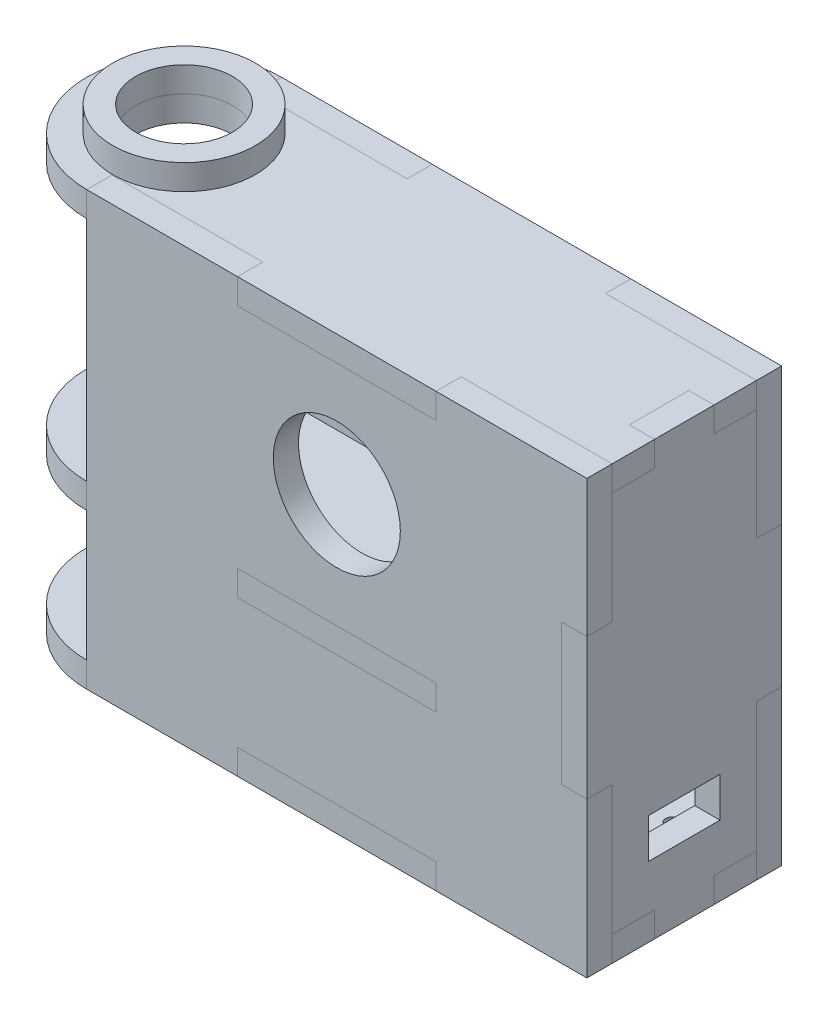
SolidWorks part; units mm, degrees
ref_plane "前视基准面" through (0, 0, 0) normal (0, 0, 1) x (1, 0, 0)
ref_plane "上视基准面" through (0, 0, 0) normal (0, 1, 0) x (1, 0, 0)
ref_plane "右视基准面" through (0, 0, 0) normal (1, 0, 0) x (0, 0, -1)
other "Configuration Table"
sketch "草图3" plane through (0, 0, 0) normal (0, 0, 1) x (1, 0, 0)
  line L0 (31.5, 17.5) -> (31.5, -37)
  line L1 (-31.5, -17.5) -> (31.5, -17.5)
  line L2 (-31.5, -17.5) -> (-31.5, 17.5)
  line L3 (-31.5, 17.5) -> (31.5, 17.5)
  line L4 (31.5, -17.5) -> (31.5, 17.5) construction
  line L5 (-31.5, -17.5) -> (31.5, 17.5) construction
  line L6 (-31.5, 17.5) -> (31.5, -17.5) construction
  line L7 (-31.5, -17.5) -> (31.5, -17.5)
  line L8 (-31.5, -17.5) -> (-31.5, -37)
  line L9 (-31.5, -37) -> (31.5, -37)
  line L10 (31.5, -17.5) -> (31.5, -37) construction
  line L11 (-12.5, -33.825) -> (12.5, -33.825)
  line L12 (-12.5, -33.825) -> (-12.5, -40.175)
  line L13 (-12.5, -40.175) -> (12.5, -40.175)
  line L14 (12.5, -33.825) -> (12.5, -40.175)
  line L15 (-12.5, -33.825) -> (12.5, -40.175) construction
  line L16 (-12.5, -40.175) -> (12.5, -33.825) construction
  line L18 (28.325, -19.75) -> (34.675, -19.75)
  line L19 (28.325, -19.75) -> (28.325, 0.25)
  line L20 (28.325, 0.25) -> (34.675, 0.25)
  line L21 (34.675, -19.75) -> (34.675, 0.25)
  line L22 (28.325, -19.75) -> (34.675, 0.25) construction
  line L23 (28.325, 0.25) -> (34.675, -19.75) construction
  line L24 (-12.5, 20.675) -> (12.5, 20.675)
  line L25 (-12.5, 20.675) -> (-12.5, 14.325)
  line L26 (-12.5, 14.325) -> (12.5, 14.325)
  line L27 (12.5, 20.675) -> (12.5, 14.325)
  line L28 (-12.5, 20.675) -> (12.5, 14.325) construction
  line L29 (-12.5, 14.325) -> (12.5, 20.675) construction
  circle A0 centre (0, 0) radius 8
  point P10 (0, -37)
  point P15 (31.5, -9.75)
  point P20 (0, 17.5)
  dimension "D1" = 20
  dimension "D5" = 16
  dimension "D2" = 25
  dimension "D3" = 25
  dimension "D4" = 54.5
  dimension "D6" = 63
  dimension "D7" = 6.35
  dimension "D8" = 6.35
extrude "凸台-拉伸2" add sketch "草图3" along normal blind 3.175 contours A0 L6 L2 L1 L19 | A0 L6 L19 L20 L0 L3 L27 L26 L25 | L18 L19 L1 L8 L9 L12 L11 L14 L0
pattern_linear "阵列(线性)1" count 2 spacing 21.35 along (0, 0, -1) of bodies 107
sketch "草图4" plane through (0, 0, -21.35) normal (0, 0, -1) x (-1, 0, 0)
  line L0 (0, -37) -> (0, -15.9125) construction
  line L2 (-12.5, -14.325) -> (12.5, -14.325)
  line L3 (-12.5, -14.325) -> (-12.5, -17.5)
  line L4 (-12.5, -17.5) -> (12.5, -17.5)
  line L5 (12.5, -14.325) -> (12.5, -17.5)
  line L6 (-12.5, -14.325) -> (12.5, -17.5) construction
  line L7 (-12.5, -17.5) -> (12.5, -14.325) construction
  line L16 (31.5, 17.5) -> (12.5, 17.5)
  line L17 (12.5, 17.5) -> (12.5, 14.325)
  line L18 (12.5, 14.325) -> (-12.5, 14.325)
  line L19 (-12.5, 14.325) -> (-12.5, 17.5)
  line L20 (-12.5, 17.5) -> (-31.5, 17.5)
  line L21 (-31.5, 17.5) -> (-31.5, 0.25)
  line L22 (-31.5, 0.25) -> (-28.325, 0.25)
  line L23 (-28.325, 0.25) -> (-28.325, -17.5)
  line L24 (-28.325, -17.5) -> (-31.5, -17.5)
  line L25 (-31.5, -17.5) -> (-31.5, -37)
  line L26 (-31.5, -37) -> (-12.5, -37)
  line L27 (-12.5, -37) -> (-12.5, -33.825)
  line L28 (-12.5, -33.825) -> (12.5, -33.825)
  line L29 (12.5, -33.825) -> (12.5, -37)
  line L30 (12.5, -37) -> (31.5, -37)
  line L31 (31.5, -37) -> (31.5, 17.5)
  line L32 (31.5, 17.5) -> (12.5, 17.5) construction
  line L33 (12.5, 17.5) -> (12.5, 14.325) construction
  line L34 (12.5, 14.325) -> (-12.5, 14.325) construction
  line L35 (-12.5, 14.325) -> (-12.5, 17.5) construction
  line L36 (-12.5, 17.5) -> (-31.5, 17.5) construction
  line L37 (-31.5, 17.5) -> (-31.5, 0.25) construction
  line L38 (-31.5, 0.25) -> (-28.325, 0.25) construction
  line L39 (-28.325, 0.25) -> (-28.325, -17.5) construction
  line L41 (-31.5, -17.5) -> (-31.5, -37) construction
  line L42 (-31.5, -37) -> (-12.5, -37) construction
  line L43 (-12.5, -37) -> (-12.5, -33.825) construction
  line L44 (-12.5, -33.825) -> (12.5, -33.825) construction
  line L45 (12.5, -33.825) -> (12.5, -37) construction
  line L46 (12.5, -37) -> (31.5, -37) construction
  line L47 (31.5, -37) -> (31.5, 17.5) construction
  line L55 (-28.325, -17.5) -> (-31.5, -17.5)
  dimension "D2" = 21.0875
  dimension "D3" = 25
  dimension "D1" = 0
extrude "切除-拉伸1" cut sketch "草图4" against normal through all contours L5 L2 L3 L4
sketch "草图5" plane through (0, 14.325, 0) normal (0, 1, 0) x (1, 0, 0)
  line L0 (-31.5, 18.175) -> (-31.5, 21.35) construction
  line L1 (-31.5, 18.175) -> (31.5, 18.175)
  line L2 (-31.5, 21.35) -> (-31.5, -3.175)
  line L3 (-31.5, 0) -> (31.5, 0)
  line L4 (12.5, 21.35) -> (-12.5, 21.35)
  line L5 (-12.5, 21.35) -> (-12.5, 18.175)
  line L6 (-12.5, 18.175) -> (12.5, 18.175)
  line L7 (12.5, 18.175) -> (12.5, 21.35)
  line L8 (12.5, 21.35) -> (-12.5, 21.35)
  line L9 (-12.5, 21.35) -> (-12.5, 18.175)
  line L10 (-12.5, 18.175) -> (12.5, 18.175)
  line L11 (12.5, 18.175) -> (12.5, 21.35)
  line L12 (12.5, 0) -> (-12.5, 0)
  line L13 (-12.5, 0) -> (-12.5, -3.175)
  line L14 (-12.5, -3.175) -> (12.5, -3.175)
  line L15 (12.5, -3.175) -> (12.5, 0)
  line L16 (12.5, 0) -> (-12.5, 0)
  line L17 (-12.5, 0) -> (-12.5, -3.175)
  line L18 (-12.5, -3.175) -> (12.5, -3.175)
  line L19 (12.5, -3.175) -> (12.5, 0)
  line L20 (31.5, 18.175) -> (31.5, 0)
  line L22 (28.325, 5.3375) -> (34.675, 5.3375)
  line L23 (28.325, 5.3375) -> (28.325, 12.8375)
  line L24 (28.325, 12.8375) -> (34.675, 12.8375)
  line L25 (34.675, 5.3375) -> (34.675, 12.8375)
  line L26 (28.325, 5.3375) -> (34.675, 12.8375) construction
  line L27 (28.325, 12.8375) -> (34.675, 5.3375) construction
  arc A0 (-31.5, -3.175) -> (-31.5, 21.35) centre (-31.5, 9.0875) cw
  point P20 (31.5, 9.0875)
  line M10 (12.5, 21.35) -> (-12.5, 21.35)
  line M11 (-12.5, 21.35) -> (-12.5, 18.175)
  line M12 (-12.5, 18.175) -> (12.5, 18.175)
  line M13 (12.5, 18.175) -> (12.5, 21.35)
  dimension "D1" = 0
  dimension "D2" = 0
extrude "凸台-拉伸3" add sketch "草图5" along normal blind 3.175 separate body contours L23 L24 L20 L1 L2 L3 L22 M12 | A0 L2 | M13 M10 M11 M12 | L18 L19 L3 L17
sketch "草图6" plane through (0, -14.325, 0) normal (0, -1, 0) x (1, 0, 0)
  line L0 (28.325, 0) -> (28.325, -18.175)
  line L4 (12.5, -18.175) -> (-12.5, -18.175)
  line L5 (-12.5, -18.175) -> (-12.5, -21.35)
  line L6 (-12.5, -21.35) -> (12.5, -21.35)
  line L7 (12.5, -21.35) -> (12.5, -18.175)
  line L8 (12.5, -18.175) -> (-12.5, -18.175)
  line L9 (-12.5, -18.175) -> (-12.5, -21.35)
  line L10 (-12.5, -21.35) -> (12.5, -21.35)
  line L11 (12.5, -21.35) -> (12.5, -18.175)
  line L12 (12.5, 0) -> (12.5, 3.175)
  line L13 (12.5, 3.175) -> (-12.5, 3.175)
  line L14 (-12.5, 3.175) -> (-12.5, 0)
  line L15 (-12.5, 0) -> (12.5, 0)
  line L16 (12.5, 0) -> (12.5, 3.175)
  line L17 (12.5, 3.175) -> (-12.5, 3.175)
  line L18 (-12.5, 3.175) -> (-12.5, 0)
  line L19 (-12.5, 0) -> (12.5, 0)
  line L33 (28.325, -12.8375) -> (28.325, -5.3375)
  line L34 (28.325, -5.3375) -> (31.5, -5.3375)
  line L35 (31.5, -5.3375) -> (31.5, 0)
  line L36 (31.5, 0) -> (12.5, 0)
  line L37 (12.5, 0) -> (12.5, 3.175)
  line L38 (12.5, 3.175) -> (-12.5, 3.175)
  line L39 (-12.5, 3.175) -> (-12.5, 0)
  line L40 (-12.5, 0) -> (-31.5, 0)
  line L41 (-31.5, 0) -> (-31.5, 3.175)
  line L42 (-31.5, -21.35) -> (-31.5, -18.175)
  line L43 (-31.5, -18.175) -> (-12.5, -18.175)
  line L44 (-12.5, -18.175) -> (-12.5, -21.35)
  line L45 (-12.5, -21.35) -> (12.5, -21.35)
  line L46 (12.5, -21.35) -> (12.5, -18.175)
  line L47 (12.5, -18.175) -> (31.5, -18.175)
  line L48 (31.5, -18.175) -> (31.5, -12.8375)
  line L49 (31.5, -12.8375) -> (28.325, -12.8375)
  line L50 (28.325, -12.8375) -> (28.325, -5.3375)
  line L51 (28.325, -5.3375) -> (31.5, -5.3375)
  line L52 (31.5, -5.3375) -> (31.5, 0)
  line L53 (31.5, 0) -> (12.5, 0)
  line L54 (12.5, 0) -> (12.5, 3.175)
  line L55 (12.5, 3.175) -> (-12.5, 3.175)
  line L56 (-12.5, 3.175) -> (-12.5, 0)
  line L57 (-12.5, 0) -> (-31.5, 0)
  line L58 (-31.5, 0) -> (-31.5, 3.175)
  line L59 (-31.5, -21.35) -> (-31.5, -18.175)
  line L60 (-31.5, -18.175) -> (-12.5, -18.175)
  line L61 (-12.5, -18.175) -> (-12.5, -21.35)
  line L62 (-12.5, -21.35) -> (12.5, -21.35)
  line L63 (12.5, -21.35) -> (12.5, -18.175)
  line L64 (12.5, -18.175) -> (31.5, -18.175)
  line L65 (31.5, -18.175) -> (31.5, -12.8375)
  line L66 (31.5, -12.8375) -> (28.325, -12.8375)
  arc A1 (-31.5, 3.175) -> (-31.5, -21.35) centre (-31.5, -9.0875) ccw
  arc A2 (-31.5, 3.175) -> (-31.5, -21.35) centre (-31.5, -9.0875) ccw
  line M27 (12.5, -18.175) -> (-12.5, -18.175)
  line M28 (-12.5, -18.175) -> (-12.5, -21.35)
  line M29 (-12.5, -21.35) -> (12.5, -21.35)
  line M30 (12.5, -21.35) -> (12.5, -18.175)
  dimension "D1" = 0
  dimension "D2" = 0
  dimension "D3" = 0
extrude "凸台-拉伸4" add sketch "草图6" along normal blind 3.175 separate body contours L58 A2 L59 L60 L64 L0 L53 L19 L57 M27 | M30 M27 M28 M29
sketch "草图7" plane through (0, -33.825, 0) normal (0, -1, 0) x (1, 0, 0)
  line L13 (-31.5, 0) -> (-31.5, 3.175)
  line L14 (-31.5, -21.35) -> (-31.5, -18.175)
  line L15 (-31.5, -18.175) -> (-12.5, -18.175)
  line L17 (-12.5, -21.35) -> (12.5, -21.35)
  line L18 (-31.5, -18.175) -> (-12.5, -18.175)
  line L19 (12.5, -18.175) -> (28.325, -18.175)
  line L20 (28.325, -18.175) -> (28.325, 0)
  line L22 (-12.5, -18.175) -> (-12.5, -21.35)
  line L23 (12.5, 3.175) -> (-12.5, 3.175)
  line L25 (-12.5, -18.175) -> (-12.5, -21.35)
  line L26 (-31.5, 0) -> (-31.5, 3.175)
  line L27 (-31.5, -21.35) -> (-31.5, -18.175)
  line L30 (-12.5, -21.35) -> (12.5, -21.35)
  line L32 (12.5, -18.175) -> (28.325, -18.175)
  line L36 (12.5, 3.175) -> (-12.5, 3.175)
  line L41 (12.5, -21.35) -> (12.5, -18.175)
  line L43 (28.325, -12.8375) -> (28.325, -5.3375)
  line L44 (31.5, -12.8375) -> (28.325, -12.8375)
  line L45 (31.5, -18.175) -> (31.5, -12.8375)
  line L46 (12.5, -18.175) -> (31.5, -18.175)
  line L47 (12.5, -21.35) -> (12.5, -18.175)
  line L48 (-12.5, -21.35) -> (12.5, -21.35)
  line L49 (-12.5, -18.175) -> (-12.5, -21.35)
  line L50 (-31.5, -18.175) -> (-12.5, -18.175)
  line L51 (-31.5, -21.35) -> (-31.5, -18.175)
  line L52 (-31.5, 0) -> (-31.5, 3.175)
  line L53 (-12.5, 0) -> (-31.5, 0)
  line L54 (-12.5, 3.175) -> (-12.5, 0)
  line L55 (12.5, 3.175) -> (-12.5, 3.175)
  line L56 (12.5, 0) -> (12.5, 3.175)
  line L57 (31.5, 0) -> (12.5, 0)
  line L58 (31.5, -5.3375) -> (31.5, 0)
  line L59 (28.325, -5.3375) -> (31.5, -5.3375)
  line L60 (28.325, -12.8375) -> (28.325, -5.3375)
  line L61 (31.5, -12.8375) -> (28.325, -12.8375)
  line L62 (31.5, -18.175) -> (31.5, -12.8375)
  line L63 (12.5, -18.175) -> (31.5, -18.175)
  line L64 (12.5, -21.35) -> (12.5, -18.175)
  line L65 (-12.5, -21.35) -> (12.5, -21.35)
  line L66 (-12.5, -18.175) -> (-12.5, -21.35)
  line L67 (-31.5, -18.175) -> (-12.5, -18.175)
  line L68 (-31.5, -21.35) -> (-31.5, -18.175)
  line L69 (-31.5, 0) -> (-31.5, 3.175)
  line L70 (-12.5, 0) -> (-31.5, 0)
  line L71 (-12.5, 3.175) -> (-12.5, 0)
  line L72 (12.5, 3.175) -> (-12.5, 3.175)
  line L73 (12.5, 0) -> (12.5, 3.175)
  line L74 (31.5, 0) -> (12.5, 0)
  line L75 (31.5, -5.3375) -> (31.5, 0)
  line L76 (28.325, -5.3375) -> (31.5, -5.3375)
  line L77 (12.5, -21.35) -> (12.5, -18.175)
  line L79 (28.325, 0) -> (12.5, 0)
  line L81 (28.325, 0) -> (12.5, 0)
  line L82 (12.5, 0) -> (12.5, 3.175)
  line L83 (12.5, 0) -> (12.5, 3.175)
  line L84 (-12.5, 3.175) -> (-12.5, 0)
  line L85 (-12.5, 3.175) -> (-12.5, 0)
  line L86 (-12.5, 0) -> (-31.5, 0)
  line L87 (-12.5, 0) -> (-31.5, 0)
  line L88 (28.325, -18.175) -> (28.325, 0)
  arc A1 (-31.5, 3.175) -> (-31.5, -21.35) centre (-31.5, -9.0875) ccw
  arc A2 (-31.5, 3.175) -> (-31.5, -21.35) centre (-31.5, -9.0875) ccw
  arc A3 (-31.5, 3.175) -> (-31.5, -21.35) centre (-31.5, -9.0875) ccw
  arc A4 (-31.5, 3.175) -> (-31.5, -21.35) centre (-31.5, -9.0875) ccw
  line M33 (-12.5, 0) -> (12.5, 0)
  line M34 (12.5, 0) -> (12.5, 3.175)
  line M35 (12.5, 3.175) -> (-12.5, 3.175)
  line M36 (-12.5, 3.175) -> (-12.5, 0)
  dimension "D1" = 0
  dimension "D2" = 0
extrude "凸台-拉伸5" add sketch "草图7" along normal blind 3.175 separate body contours L26 A2 L27 L18 L25 L30 L77 L32 L88 L81 L87 M33 | M36 M33 M34 M35 | L88 L76 L75 L74 | L88 L63 L62 L61
sketch "草图8" plane through (28.325, 0, 0) normal (1, 0, 0) x (0, 0, -1)
  line L38 (12.8375, -33.825) -> (5.3375, -33.825) construction
  line L39 (5.3375, -33.825) -> (5.3375, -37) construction
  line L40 (5.3375, -37) -> (12.8375, -37) construction
  line L41 (12.8375, -37) -> (12.8375, -33.825) construction
  line L43 (21.35, -17.5) -> (21.35, 0.25) construction
  line L44 (21.35, 0.25) -> (18.175, 0.25) construction
  line L45 (18.175, 0.25) -> (18.175, -17.5) construction
  line L46 (18.175, -17.5) -> (21.35, -17.5) construction
  line L47 (0, -17.5) -> (0, 0.25) construction
  line L48 (0, 0.25) -> (-3.175, 0.25) construction
  line L49 (-3.175, 0.25) -> (-3.175, -17.5) construction
  line L50 (-3.175, -17.5) -> (0, -17.5) construction
  line L51 (5.3375, 14.325) -> (12.8375, 14.325) construction
  line L52 (12.8375, 14.325) -> (12.8375, 17.5) construction
  line L53 (12.8375, 17.5) -> (5.3375, 17.5) construction
  line L54 (5.3375, 17.5) -> (5.3375, 14.325) construction
  line L55 (12.8375, -33.825) -> (5.3375, -33.825)
  line L56 (5.3375, -33.825) -> (5.3375, -37)
  line L57 (5.3375, -37) -> (12.8375, -37)
  line L58 (12.8375, -37) -> (12.8375, -33.825)
  line L59 (21.35, -17.5) -> (21.35, 0.25)
  line L60 (21.35, 0.25) -> (18.175, 0.25)
  line L61 (18.175, 0.25) -> (18.175, -17.5)
  line L62 (18.175, -17.5) -> (21.35, -17.5)
  line L63 (0, -17.5) -> (0, 0.25)
  line L64 (0, 0.25) -> (-3.175, 0.25)
  line L65 (-3.175, 0.25) -> (-3.175, -17.5)
  line L66 (-3.175, -17.5) -> (0, -17.5)
  line L67 (5.3375, 14.325) -> (12.8375, 14.325)
  line L68 (12.8375, 14.325) -> (12.8375, 17.5)
  line L69 (12.8375, 17.5) -> (5.3375, 17.5)
  line L70 (5.3375, 17.5) -> (5.3375, 14.325)
  line L71 (18.175, -17.5) -> (18.175, -37) construction
  line L72 (0, 14.325) -> (18.175, 14.325)
  line L73 (0, 14.325) -> (0, -33.825)
  line L74 (0, -33.825) -> (18.175, -33.825)
  line L75 (18.175, 14.325) -> (18.175, -33.825)
extrude "凸台-拉伸6" add sketch "草图8" along normal up to surface (3.175 mm away) separate body
sketch "草图12" plane through (0, -37, 0) normal (0, -1, 0) x (1, 0, 0)
  line L0 (31.5, -9.0875) -> (-43.7625, -9.0875) construction
  line L1 (-16.3955, -12.8375) -> (-16.3955, -5.3375) construction
  line L3 (31.5, -5.3375) -> (31.5, -12.8375) construction
  line L8 (22.7545, -9.0875) -> (26.2045, -9.0875) construction
  line L9 (-12.9455, -16.6875) -> (22.7545, -16.6875)
  line L10 (-12.9455, -16.6875) -> (-12.9455, -1.4875)
  line L11 (-12.9455, -1.4875) -> (22.7545, -1.4875)
  line L12 (22.7545, -16.6875) -> (22.7545, -1.4875)
  line L13 (-12.9455, -16.6875) -> (22.7545, -1.4875) construction
  line L14 (-12.9455, -1.4875) -> (22.7545, -16.6875) construction
  line L15 (26.2045, -12.8375) -> (26.2045, -5.3375) construction
  line L16 (4.9045, -9.0875) -> (4.9045, -3.4951) construction
  arc A0 (-31.5, 3.175) -> (-31.5, -21.35) centre (-31.5, -9.0875) ccw construction
  circle A1 centre (26.2045, -5.3375) radius 0.795
  circle A2 centre (26.2045, -12.8375) radius 0.795
  circle A3 centre (-16.3955, -12.8375) radius 0.795
  circle A4 centre (-16.3955, -5.3375) radius 0.795
  point P7 (4.9045, -9.0875)
  dimension "D1" = 15.2
  dimension "D4" = 1.59
  dimension "D2" = 35.7
  dimension "D3" = 3.45
  dimension "D5" = 7.5
extrude "切除-拉伸2" cut sketch "草图12" against normal through all
sketch "草图14" plane through (0, -33.825, 0) normal (0, 1, 0) x (1, 0, 0)
  line L0 (-12.9455, 16.6875) -> (22.7545, 1.4875) construction
  line L1 (4.9045, 9.0875) -> (27.6217, 9.0875) construction
  line L2 (28.325, 18.175) -> (28.325, 0)
  line L3 (4.9045, 9.0875) -> (4.9045, 14.677) construction
  line L4 (22.7545, 16.6875) -> (-12.9455, 16.6875)
  line L5 (22.7545, 1.4875) -> (22.7545, 16.6875)
  line L6 (-12.9455, 1.4875) -> (22.7545, 1.4875)
  line L7 (-12.9455, 16.6875) -> (-12.9455, 1.4875)
  line L8 (22.7545, 16.6875) -> (-12.9455, 16.6875)
  line L9 (22.7545, 1.4875) -> (22.7545, 16.6875)
  line L10 (-12.9455, 1.4875) -> (22.7545, 1.4875)
  line L11 (-12.9455, 16.6875) -> (-12.9455, 1.4875)
  line L12 (-18.5161, 5.3375) -> (-18.5161, 12.8375)
  line L13 (-18.5161, 18.175) -> (-18.5161, 0)
  line L14 (-12.5, 0) -> (12.5, 0)
  line L15 (12.5, 18.175) -> (-12.5, 18.175)
  line L17 (-31.5, -3.175) -> (-31.5, 0)
  line L18 (-31.5, 0) -> (-12.5, 0)
  line L19 (-12.5, 0) -> (-12.5, -3.175)
  line L20 (-12.5, -3.175) -> (12.5, -3.175)
  line L21 (12.5, -3.175) -> (12.5, 0)
  line L22 (12.5, 0) -> (31.5, 0)
  line L23 (31.5, 0) -> (31.5, 5.3375)
  line L24 (31.5, 5.3375) -> (28.325, 5.3375)
  line L25 (28.325, 5.3375) -> (28.325, 12.8375)
  line L26 (28.325, 12.8375) -> (31.5, 12.8375)
  line L27 (31.5, 12.8375) -> (31.5, 18.175)
  line L28 (31.5, 18.175) -> (12.5, 18.175)
  line L29 (12.5, 18.175) -> (12.5, 21.35)
  line L30 (12.5, 21.35) -> (-12.5, 21.35)
  line L31 (-12.5, 21.35) -> (-12.5, 18.175)
  line L32 (-12.5, 18.175) -> (-31.5, 18.175)
  line L33 (-31.5, 18.175) -> (-31.5, 21.35)
  line L34 (-31.5, -3.175) -> (-31.5, 0)
  line L35 (-31.5, 0) -> (-12.5, 0)
  line L36 (-12.5, 0) -> (-12.5, -3.175)
  line L37 (-12.5, -3.175) -> (12.5, -3.175)
  line L38 (12.5, -3.175) -> (12.5, 0)
  line L39 (12.5, 0) -> (31.5, 0)
  line L40 (31.5, 0) -> (31.5, 5.3375)
  line L41 (31.5, 5.3375) -> (28.325, 5.3375)
  line L42 (28.325, 5.3375) -> (28.325, 12.8375)
  line L43 (28.325, 12.8375) -> (31.5, 12.8375)
  line L44 (31.5, 12.8375) -> (31.5, 18.175)
  line L45 (31.5, 18.175) -> (12.5, 18.175)
  line L46 (12.5, 18.175) -> (12.5, 21.35)
  line L47 (12.5, 21.35) -> (-12.5, 21.35)
  line L48 (-12.5, 21.35) -> (-12.5, 18.175)
  line L49 (-12.5, 18.175) -> (-31.5, 18.175)
  line L50 (-31.5, 18.175) -> (-31.5, 21.35)
  arc A1 (-31.5, 21.35) -> (-31.5, -3.175) centre (-31.5, 9.0875) ccw
  arc A2 (-31.5, 21.35) -> (-31.5, -3.175) centre (-31.5, 9.0875) ccw
  circle A3 centre (26.2045, 5.3375) radius 0.795
  circle A4 centre (26.2045, 5.3375) radius 0.795
  circle A5 centre (-16.3955, 5.3375) radius 0.795
  circle A6 centre (-16.3955, 5.3375) radius 0.795
  circle A7 centre (-16.3955, 12.8375) radius 0.795
  circle A8 centre (-16.3955, 12.8375) radius 0.795
  circle A9 centre (26.2045, 12.8375) radius 0.795
  circle A10 centre (26.2045, 12.8375) radius 0.795
  circle M28 centre (-16.3955, 5.3375) radius 0.795
  circle M29 centre (-16.3955, 12.8375) radius 0.795
  circle M30 centre (26.2045, 12.8375) radius 0.795
  circle M31 centre (26.2045, 5.3375) radius 0.795
  line M32 (-12.9455, 16.6875) -> (22.7545, 16.6875)
  line M33 (22.7545, 16.6875) -> (22.7545, 1.4875)
  line M34 (22.7545, 1.4875) -> (-12.9455, 1.4875)
  line M35 (-12.9455, 1.4875) -> (-12.9455, 16.6875)
  line M37 (-31.5, 0) -> (-12.5, 0)
  line M41 (12.5, 0) -> (31.5, 0)
  line M44 (28.325, 5.3375) -> (28.325, 12.8375)
  line M47 (31.5, 18.175) -> (12.5, 18.175)
  line M51 (-12.5, 18.175) -> (-31.5, 18.175)
  dimension "D1" = 0
  dimension "D2" = 0
  dimension "D3" = 0
  dimension "D4" = 0
  dimension "D5" = 0
  dimension "D6" = 0
extrude "凸台-拉伸9" add sketch "草图14" along normal blind 3.175 separate body contours L15 L13 L12 L14 L2 M47 M51 M37 M41 M44 M29 M31 M35 M32 M33 M34 M30 M28
sketch "草图9" plane through (0, 17.5, 0) normal (0, 1, 0) x (1, 0, 0)
  arc A0 (-31.5, 21.35) -> (-31.5, -3.175) centre (-31.5, 9.0875) ccw construction
  arc A1 (-31.5, 21.35) -> (-31.5, -3.175) centre (-31.5, 9.0875) ccw
  circle A2 centre (-31.5, 9.0875) radius 9
  dimension "D1" = 18
extrude "凸台-拉伸7" add sketch "草图9" along normal blind 3.175 separate body contours A2
sketch "草图10" plane through (0, -37, 0) normal (0, -1, 0) x (1, 0, 0)
  arc A0 (-31.5, 3.175) -> (-31.5, -21.35) centre (-31.5, -9.0875) ccw construction
  circle A1 centre (-31.5, -9.0875) radius 9
  circle A2 centre (-31.5, -9.0875) radius 9
  arc A3 (-31.5, 3.175) -> (-31.5, -21.35) centre (-31.5, -9.0875) ccw
  dimension "D1" = 0
extrude "凸台-拉伸8" add sketch "草图10" along normal blind 3.175 separate body contours A2
sketch "草图15" plane through (0, 20.675, 0) normal (0, 1, 0) x (1, 0, 0)
  circle A0 centre (-31.5, 9.0875) radius 6.1
  circle A1 centre (-31.5, 9.0875) radius 9
  circle A2 centre (-31.5, 9.0875) radius 9
  dimension "D2" = 12.2
  dimension "D1" = 0
extrude "切除-拉伸3" cut sketch "草图15" against normal through all contours A0
sketch "草图16" plane through (31.5, 0, 0) normal (1, 0, 0) x (0, 0, -1)
  line L0 (0, -25.6625) -> (18.175, -25.6625) construction
  line L1 (0, -17.5) -> (0, -33.825) construction
  line L2 (18.175, -17.5) -> (18.175, -37) construction
  line L4 (4.5875, -28.1625) -> (13.5875, -28.1625)
  line L5 (4.5875, -28.1625) -> (4.5875, -23.1625)
  line L6 (4.5875, -23.1625) -> (13.5875, -23.1625)
  line L7 (13.5875, -28.1625) -> (13.5875, -23.1625)
  line L8 (4.5875, -28.1625) -> (13.5875, -23.1625) construction
  line L9 (4.5875, -23.1625) -> (13.5875, -28.1625) construction
  point P6 (9.0875, -25.6625)
extrude "切除-拉伸4" cut sketch "草图16" against normal through all both and the other way through all
